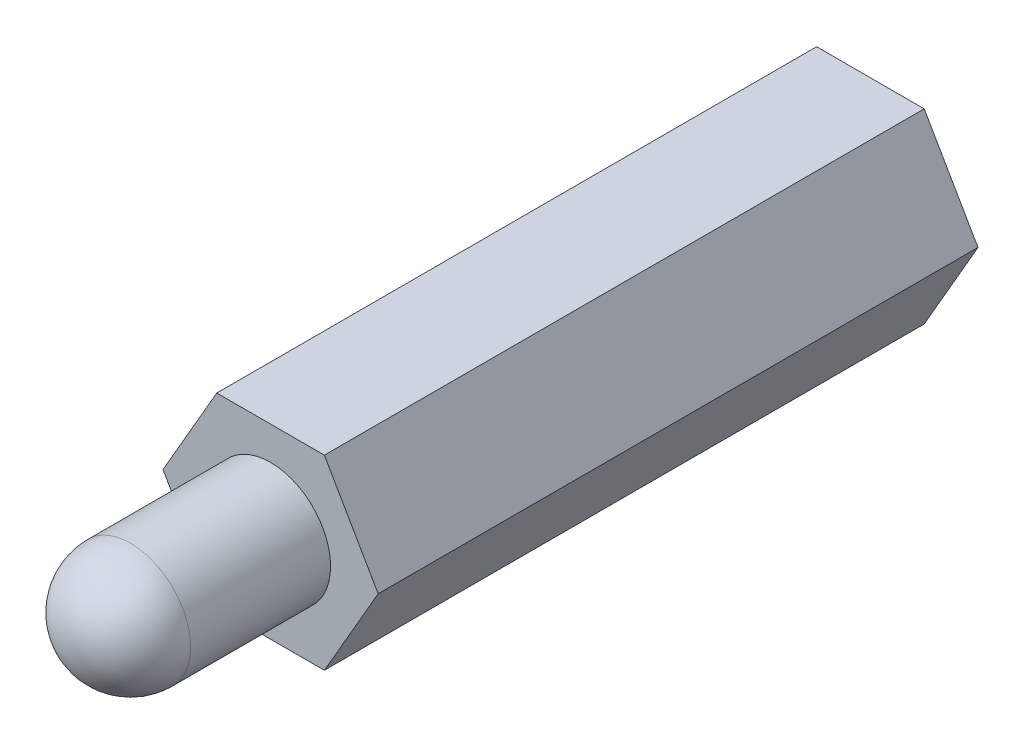
SolidWorks part; units mm, degrees
material "2A12"
ref_plane "前视基准面" through (0, 0, 0) normal (0, 0, 1) x (1, 0, 0)
ref_plane "上视基准面" through (0, 0, 0) normal (0, 1, 0) x (1, 0, 0)
ref_plane "右视基准面" through (0, 0, 0) normal (1, 0, 0) x (0, 0, -1)
sketch "草图1" plane through (0, 0, 0) normal (0, 0, 1) x (1, 0, 0)
  line L1 (2.6905, 0) -> (1.3452, 2.33)
  line L2 (1.3452, 2.33) -> (-1.3452, 2.33)
  line L3 (-1.3452, 2.33) -> (-2.6905, 0)
  line L4 (-2.6905, 0) -> (-1.3452, -2.33)
  line L5 (-1.3452, -2.33) -> (1.3452, -2.33)
  line L6 (1.3452, -2.33) -> (2.6905, 0)
  circle A0 centre (0, 0) radius 2.33 construction
  dimension "D1" = 4.66
extrude "凸台-拉伸1" add sketch "草图1" along normal blind 15
sketch "草图2" plane through (0, 0, 15) normal (0, 0, 1) x (1, 0, 0)
  circle A0 centre (0, 0) radius 1.5
  dimension "D1" = 3
extrude "凸台-拉伸2" add sketch "草图2" along normal blind 5
fillet "圆角1" radius 1.5 1 edges at (1.5, 0, 20)
sketch "草图3" plane through (0, 0, 0) normal (0, 0, -1) x (-1, 0, 0)
  circle A0 centre (0, 0) radius 1.25
  dimension "D1" = 2.5
extrude "切除-拉伸1" cut sketch "草图3" against normal blind 10
